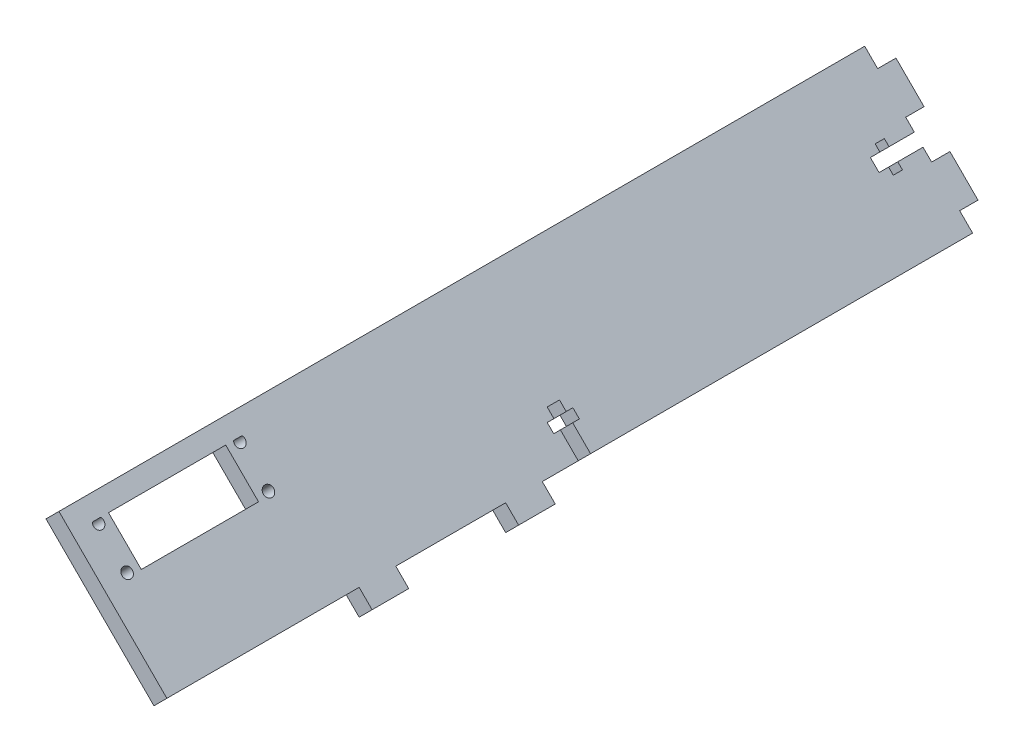
SolidWorks part; units mm, degrees
ref_plane "Front Plane" through (0, 0, 0) normal (0, 0, 1) x (1, 0, 0)
ref_plane "Top Plane" through (0, 0, 0) normal (0, 1, 0) x (1, 0, 0)
ref_plane "Right Plane" through (0, 0, 0) normal (1, 0, 0) x (0, 0, -1)
sketch "Sketch2" plane through (0, 0, 0) normal (0, 0, 1) x (1, 0, 0)
  line L0 (-71.1005, -13.7123) -> (-75.5906, -18.2024)
  line L1 (-71.1005, -13.7123) -> (-42.6562, -42.1565)
  line L2 (-75.5906, -18.2024) -> (-47.1463, -46.6467)
  line L3 (-42.6562, -42.1565) -> (-47.1463, -46.6467)
  line L4 (-75.5906, -18.2024) -> (-65.8586, -27.9344) construction
  line L5 (-61.3685, -23.4443) -> (-71.1005, -13.7123) construction
  line L6 (-47.1463, -46.6467) -> (-42.6562, -42.1565) construction
  line L7 (-71.1005, -13.7123) -> (-75.5906, -18.2024) construction
extrude "Base Extrusion" add sketch "Sketch2" along normal blind 279.4
sketch "Sketch3" plane through (-46.8965, -46.8965, 0) normal (-0.7071, -0.7071, 0) x (0, 0, 1)
  line L0 (0, 20.4664) -> (24.1393, 20.4664) construction
  line L1 (0, 40.5796) -> (0, 0.3533) construction
  line B0 (0, 22.6) -> (0, 18.3328)
  line B1 (11.938, 18.3328) -> (11.938, 16.0214)
  line B2 (11.938, 16.0214) -> (8.763, 16.0214)
  line B3 (8.763, 16.0214) -> (8.763, 18.3328)
  line B4 (8.763, 18.3328) -> (0, 18.3328)
  line B5 (11.938, 18.3328) -> (15.24, 18.3328)
  line B6 (15.24, 18.3328) -> (15.24, 22.6)
  line B7 (11.938, 22.6) -> (15.24, 22.6)
  line B8 (8.763, 22.6) -> (0, 22.6)
  line B9 (8.763, 24.9114) -> (8.763, 22.6)
  line B10 (11.938, 24.9114) -> (8.763, 24.9114)
  line B11 (11.938, 22.6) -> (11.938, 24.9114)
sketch_block_instance "TSlot-1"
sketch_block "TSlot" parameters "D1"=3.302, "D2"=3.175
extrude "Base T Slot" cut sketch "Sketch3" against normal through all
sketch "Sketch4" plane through (0, 0, 0) normal (0, 0, -1) x (-1, 0, 0)
  line L0 (75.5906, -18.2024) -> (65.8586, -27.9344) construction
  line L1 (65.8586, -27.9344) -> (61.3685, -23.4443) construction
  line L2 (61.3685, -23.4443) -> (71.1005, -13.7123) construction
  line L3 (71.1005, -13.7123) -> (75.5906, -18.2024) construction
  line L4 (42.6562, -42.1565) -> (52.3882, -32.4245) construction
  line L5 (52.3882, -32.4245) -> (56.8783, -36.9147) construction
  line L6 (56.8783, -36.9147) -> (47.1463, -46.6467) construction
  line L7 (47.1463, -46.6467) -> (42.6562, -42.1565) construction
  line L8 (75.5906, -18.2024) -> (65.8586, -27.9344)
  line L9 (65.8586, -27.9344) -> (61.3685, -23.4443)
  line L10 (61.3685, -23.4443) -> (71.1005, -13.7123)
  line L11 (71.1005, -13.7123) -> (75.5906, -18.2024)
  line L12 (42.6562, -42.1565) -> (52.3882, -32.4245)
  line L13 (52.3882, -32.4245) -> (56.8783, -36.9147)
  line L14 (56.8783, -36.9147) -> (47.1463, -46.6467)
  line L15 (47.1463, -46.6467) -> (42.6562, -42.1565)
extrude "Base Tabs" add sketch "Sketch4" along normal blind 6.35
sketch "Sketch5" plane through (-42.4064, -42.4064, 0) normal (0.7071, 0.7071, 0) x (0, 0, -1)
  line L1 (-266.7, 44.5623) -> (-226.06, 44.5623)
  line L2 (-266.7, 44.5623) -> (-266.7, 24.4963)
  line L3 (-266.7, 24.4963) -> (-226.06, 24.4963)
  line L4 (-226.06, 44.5623) -> (-226.06, 24.4963)
  line L5 (-279.4, 0.3533) -> (-279.4, 40.5796) construction
  line L8 (-165.1552, 44.5623) -> (-139.1365, 44.5623) construction
  line L9 (-139.1365, 24.4963) -> (-164.2745, 24.4963) construction
  dimension "D1" = 40.64
  dimension "D2" = 12.7
  dimension "D3" = 20.066
extrude "Servo Slot" cut sketch "Sketch5" against normal through all
sketch "Sketch6" plane through (-42.4064, -42.4064, 0) normal (0.7071, 0.7071, 0) x (0, 0, -1)
  line L0 (-183.9541, 32.5379) -> (-125.6675, 32.5379) construction
  line L14 (-266.7, 40.5796) -> (-266.7, 24.4963) construction
  arc A0 (-272.1243, 38.2593) -> (-272.1243, 40.7993) centre (-270.88, 39.5293) ccw construction
  arc A1 (-220.6357, 40.7993) -> (-220.6357, 38.2593) centre (-221.88, 39.5293) ccw construction
  circle A8 centre (-270.88, 39.5293) radius 1.778
  circle A9 centre (-270.88, 25.5466) radius 1.778
  circle A10 centre (-221.88, 39.5293) radius 1.778
  circle A11 centre (-221.88, 25.5466) radius 1.778
  point P26 (-266.7, 32.5379)
extrude "Servo Mounting Holes" cut sketch "Sketch6" against normal through all
sketch "Sketch7" plane through (0, 0, 279.4) normal (0, 0, 1) x (1, 0, 0)
  line L0 (-47.1463, -46.6467) -> (-42.6562, -42.1565)
  line L1 (-47.1463, -46.6467) -> (-42.6562, -51.1368)
  line L2 (-42.6562, -42.1565) -> (-38.1661, -46.6467)
  line L3 (-42.6562, -51.1368) -> (-38.1661, -46.6467)
  line L4 (-74.919, -83.3995) -> (-4.4901, -12.9707) construction
  line L5 (-75.5906, -18.2024) -> (-71.1005, -13.7123)
  line L6 (-75.5906, -18.2024) -> (-80.0807, -13.7123)
  line L7 (-71.1005, -13.7123) -> (-75.5906, -9.2222)
  line L8 (-80.0807, -13.7123) -> (-75.5906, -9.2222)
extrude "Filler Extrusion to Funnel Support" add sketch "Sketch7" against normal up to surface (279.4 mm away)
sketch "Sketch8" plane through (-42.4064, -42.4064, 0) normal (0.7071, 0.7071, 0) x (0.7071, -0.7071, 0)
  line L0 (28.1183, -134.62) -> (-82.975, -134.62) construction
  line L3 (5.9967, -279.4) -> (5.9967, -212.725) construction
  line B0 (5.9967, -136.7536) -> (5.9967, -132.4864)
  line B1 (-5.9413, -132.4864) -> (-5.9413, -130.175)
  line B2 (-5.9413, -130.175) -> (-2.7663, -130.175)
  line B3 (-2.7663, -130.175) -> (-2.7663, -132.4864)
  line B4 (-2.7663, -132.4864) -> (5.9967, -132.4864)
  line B5 (-5.9413, -132.4864) -> (-9.2433, -132.4864)
  line B6 (-9.2433, -132.4864) -> (-9.2433, -136.7536)
  line B7 (-5.9413, -136.7536) -> (-9.2433, -136.7536)
  line B8 (-2.7663, -136.7536) -> (5.9967, -136.7536)
  line B9 (-2.7663, -139.065) -> (-2.7663, -136.7536)
  line B10 (-5.9413, -139.065) -> (-2.7663, -139.065)
  line B11 (-5.9413, -136.7536) -> (-5.9413, -139.065)
sketch_block_instance "TSlot-2"
extrude "Side T Slot" cut sketch "Sketch8" against normal through all
sketch "Sketch9" plane through (4.2403, -4.2403, 0) normal (0.7071, -0.7071, 0) x (-0.7071, -0.7071, 0)
  line L0 (49.5253, -247.9715) -> (49.5253, -199.7444) construction
  line L1 (66.3217, -136.7536) -> (66.3217, -279.4) construction
  line L2 (66.3217, -212.725) -> (59.9717, -212.725)
  line L3 (66.3217, -212.725) -> (66.3217, -200.025)
  line L4 (66.3217, -200.025) -> (59.9717, -200.025)
  line L5 (59.9717, -212.725) -> (59.9717, -200.025)
  line L6 (59.9717, -136.7536) -> (59.9717, -279.4) construction
  line L7 (66.3217, 0) -> (66.3217, -132.4864) construction
  line L8 (66.3217, -161.925) -> (59.9717, -161.925)
  line L9 (66.3217, -161.925) -> (66.3217, -149.225)
  line L10 (66.3217, -149.225) -> (59.9717, -149.225)
  line L11 (59.9717, -161.925) -> (59.9717, -149.225)
  line L12 (59.9717, 0) -> (59.9717, -132.4864) construction
  line L13 (104.7498, -180.975) -> (30.8469, -180.975) construction
  line L14 (66.3217, -279.4) -> (59.9717, -279.4) construction
  line L15 (41.5779, -82.55) -> (59.9717, -82.55) construction
  dimension "D1" = 12.7
  dimension "D2" = 19.05
extrude "Side Tabs" add sketch "Sketch9" along normal up to surface (6.35 mm away)
